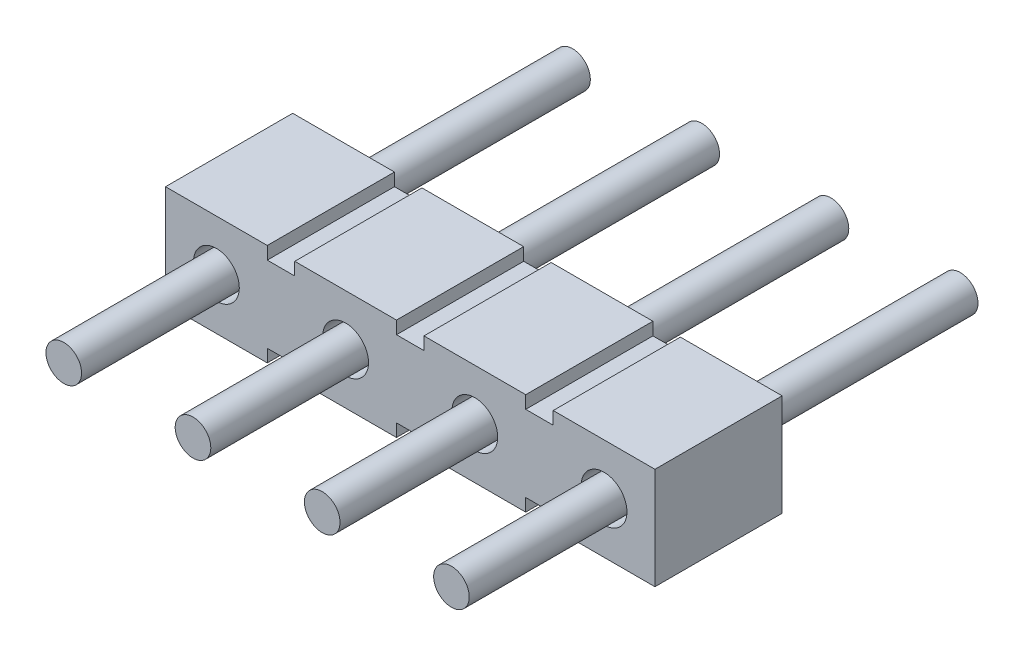
SolidWorks part; units mm, degrees
ref_plane "Ön Düzlem" through (0, 0, 0) normal (0, 0, 1) x (1, 0, 0)
ref_plane "Üst Düzlem" through (0, 0, 0) normal (0, 1, 0) x (1, 0, 0)
ref_plane "Sağ Düzlem" through (0, 0, 0) normal (1, 0, 0) x (0, 0, -1)
sketch "Çizim1" plane through (0, 0, 0) normal (0, 0, 1) x (1, 0, 0)
  circle A0 centre (0, 0) radius 0.35
  circle A1 centre (2.54, 0) radius 0.35
  circle A2 centre (5.08, 0) radius 0.35
  circle A3 centre (7.62, 0) radius 0.35
  dimension "D1" = 0.7
  dimension "D3" = 2.54
  dimension "D2" = 4
extrude "Yükseklik-Ekstrüzyon1" add sketch "Çizim1" along normal blind 10
sketch "Çizim2" plane through (0, 0, 10) normal (0, 0, 1) x (1, 0, 0)
ref_plane "Düzlem1" through (0, 0, 7) normal (0, 0, 1) x (1, 0, 0)
sketch "Çizim3" plane through (0, 0, 7) normal (0, 0, 1) x (1, 0, 0)
  line L0 (1.54, 1) -> (3.54, 1)
  line L1 (-1, 1) -> (1, 1)
  line L2 (-1, 1) -> (-1, -1)
  line L3 (-1, -1) -> (1, -1)
  line L4 (1, 1) -> (1, 0.75)
  line L5 (-1, 1) -> (1, -1) construction
  line L6 (-1, -1) -> (1, 1) construction
  line L7 (1.54, 1) -> (1.54, 0.75)
  line L8 (1.54, -1) -> (3.54, -1)
  line L9 (3.54, 1) -> (3.54, 0.75)
  line L10 (1.54, 1) -> (3.54, -1) construction
  line L11 (1.54, -1) -> (3.54, 1) construction
  line L12 (4.08, 1) -> (6.08, 1)
  line L13 (4.08, 1) -> (4.08, 0.75)
  line L14 (4.08, -1) -> (6.08, -1)
  line L15 (6.08, 1) -> (6.08, 0.75)
  line L16 (4.08, 1) -> (6.08, -1) construction
  line L17 (4.08, -1) -> (6.08, 1) construction
  line L18 (6.62, 1) -> (8.62, 1)
  line L19 (6.62, 1) -> (6.62, 0.75)
  line L20 (6.62, -1) -> (8.62, -1)
  line L21 (8.62, 1) -> (8.62, -1)
  line L22 (6.62, 1) -> (8.62, -1) construction
  line L23 (6.62, -1) -> (8.62, 1) construction
  line L24 (1, 0.75) -> (1.54, 0.75)
  line L25 (0, 0) -> (0.7523, 0) construction
  line L26 (1, -0.75) -> (1.54, -0.75)
  line L27 (3.54, 0.75) -> (4.08, 0.75)
  line L28 (3.54, -0.75) -> (4.08, -0.75)
  line L29 (6.08, -0.75) -> (6.62, -0.75)
  line L30 (6.08, 0.75) -> (6.62, 0.75)
  line L31 (1, -0.75) -> (1, -1)
  line L32 (1.54, -0.75) -> (1.54, -1)
  line L33 (3.54, -0.75) -> (3.54, -1)
  line L34 (4.08, -0.75) -> (4.08, -1)
  line L35 (6.08, -0.75) -> (6.08, -1)
  line L36 (6.62, -0.75) -> (6.62, -1)
  circle A0 centre (0, 0) radius 0.35 construction
  circle A1 centre (0, 0) radius 0.35 construction
  circle A2 centre (0, 0) radius 0.45
  circle A3 centre (2.54, 0) radius 0.45
  circle A4 centre (5.08, 0) radius 0.45
  circle A5 centre (7.62, 0) radius 0.45
  circle A6 centre (2.54, 0) radius 0.35 construction
  circle A7 centre (5.08, 0) radius 0.35 construction
  circle A8 centre (7.62, 0) radius 0.35 construction
  dimension "D2" = 2.54
  dimension "D3" = 2
  dimension "D4" = 0.54
  dimension "D5" = 1.5
  dimension "D1" = 0.1
extrude "Yükseklik-Ekstrüzyon2" add sketch "Çizim3" against normal blind 2.5 separate body
